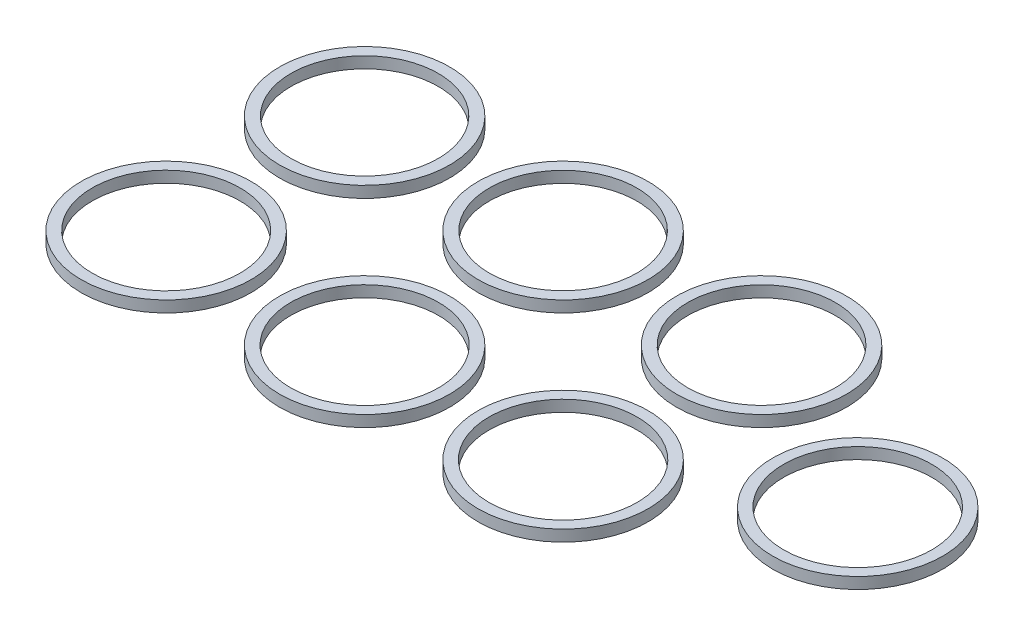
SolidWorks part; units mm, degrees
ref_plane "Front Plane" through (0, 0, 0) normal (0, 0, 1) x (1, 0, 0)
ref_plane "Top Plane" through (0, 0, 0) normal (0, 1, 0) x (1, 0, 0)
ref_plane "Right Plane" through (0, 0, 0) normal (1, 0, 0) x (0, 0, -1)
sketch "Sketch1" plane through (0, 0, 0) normal (0, 1, 0) x (1, 0, 0)
  circle A0 centre (0, 0) radius 26
  circle A1 centre (0, 0) radius 30
  circle A2 centre (70, 0) radius 30
  circle A3 centre (140, 0) radius 30
  circle A4 centre (70, -70) radius 30
  circle A5 centre (140, -70) radius 30
  circle A6 centre (0, -70) radius 30
  circle A7 centre (70, 0) radius 26.025
  circle A8 centre (140, 0) radius 26.05
  circle A9 centre (0, -70) radius 26.075
  circle A10 centre (70, -70) radius 26.1
  circle A11 centre (140, -70) radius 26.125
  circle A12 centre (206.4242, -32.5077) radius 30
  circle A13 centre (206.4242, -32.5077) radius 26.15
  dimension "D1" = 60
  dimension "D2" = 52
  dimension "D5" = 52.05
  dimension "D6" = 52.1
  dimension "D7" = 52.15
  dimension "D8" = 52.2
  dimension "D9" = 52.25
  dimension "D10" = 52.3
  dimension "D3" = 3
  dimension "D4" = 2
extrude "Boss-Extrude1" add sketch "Sketch1" along normal blind 4
